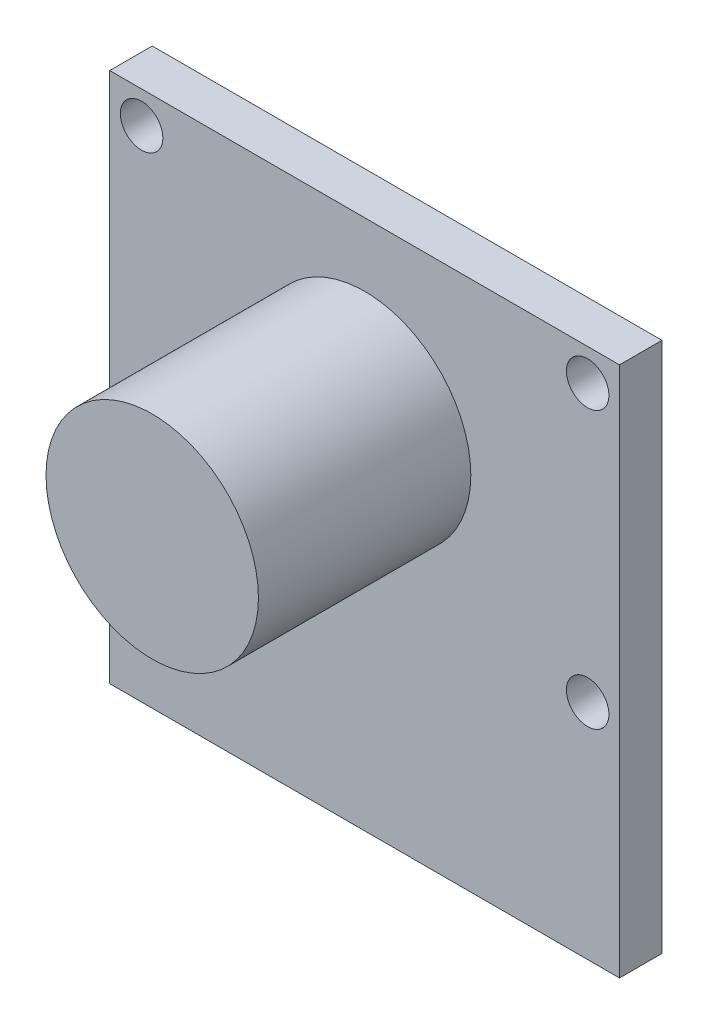
SolidWorks part; units mm, degrees
ref_plane "前视基准面" through (0, 0, 0) normal (0, 0, 1) x (1, 0, 0)
ref_plane "上视基准面" through (0, 0, 0) normal (0, 1, 0) x (1, 0, 0)
ref_plane "右视基准面" through (0, 0, 0) normal (1, 0, 0) x (0, 0, -1)
other "Configuration Table"
sketch "草图1" plane through (0, 0, 0) normal (0, 0, 1) x (1, 0, 0)
  line L1 (0, 0) -> (-24, 0)
  line L2 (0, 0) -> (0, 25)
  line L3 (0, 25) -> (-24, 25)
  line L4 (-24, 0) -> (-24, 25)
  line L5 (-22.5, 23.5) -> (-1.5, 23.5) construction
  line L6 (-22.5, 23.5) -> (-22.5, 10.5) construction
  line L7 (-22.5, 10.5) -> (-1.5, 10.5) construction
  line L8 (-1.5, 23.5) -> (-1.5, 10.5) construction
  circle A0 centre (-22.5, 23.5) radius 1
  circle A1 centre (-22.5, 10.5) radius 1
  circle A2 centre (-1.5, 10.5) radius 1
  circle A3 centre (-1.5, 23.5) radius 1
  dimension "D7" = 2
  dimension "D8" = 2
  dimension "D9" = 2
  dimension "D10" = 2
  dimension "D1" = 25
  dimension "D2" = 24
  dimension "D3" = 21
  dimension "D4" = 13
  dimension "D5" = 1.5
  dimension "D6" = 1.5
extrude "凸台-拉伸1" add sketch "草图1" along normal blind 2
sketch "草图2" plane through (0, 0, 2) normal (0, 0, 1) x (1, 0, 0)
  circle A0 centre (-12, 17) radius 5
  circle A1 centre (-22.5, 23.5) radius 1 construction
  circle A2 centre (-22.5, 10.5) radius 1 construction
  circle A3 centre (-1.5, 10.5) radius 1 construction
  circle A4 centre (-1.5, 23.5) radius 1 construction
  circle A5 centre (-22.5, 23.5) radius 1 construction
  circle A6 centre (-22.5, 10.5) radius 1 construction
  circle A7 centre (-1.5, 10.5) radius 1 construction
  circle A8 centre (-1.5, 23.5) radius 1 construction
  dimension "D3" = 10
  dimension "D1" = 10.5
  dimension "D2" = 6.5
extrude "凸台-拉伸2" add sketch "草图2" along normal blind 10
